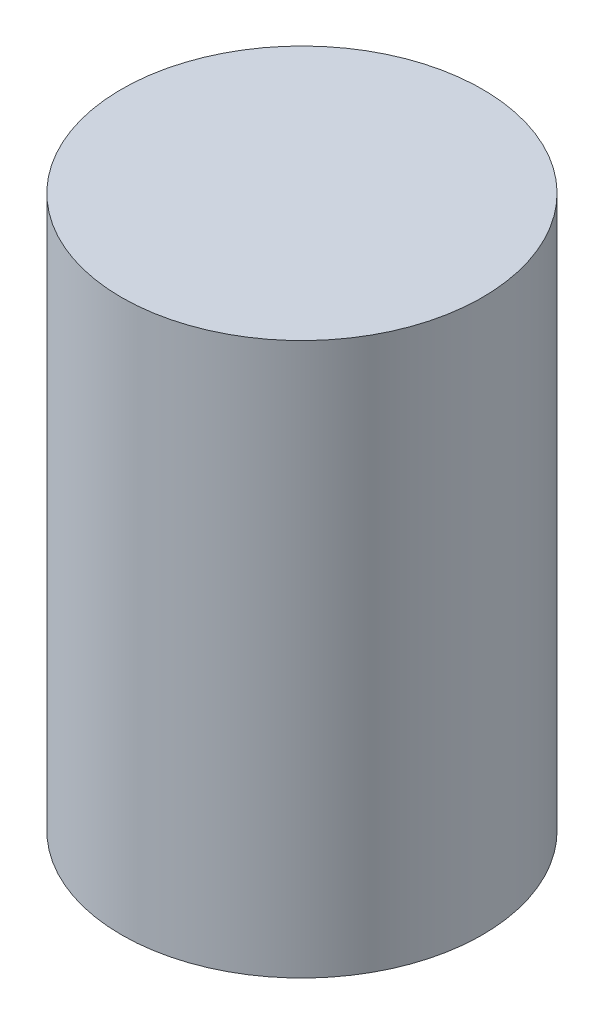
SolidWorks part; units mm, degrees
ref_plane "Front Plane" through (0, 0, 0) normal (0, 0, 1) x (1, 0, 0)
ref_plane "Top Plane" through (0, 0, 0) normal (0, 1, 0) x (1, 0, 0)
ref_plane "Right Plane" through (0, 0, 0) normal (1, 0, 0) x (0, 0, -1)
sketch "Sketch1" plane through (0, 0, 0) normal (0, 1, 0) x (1, 0, 0)
  circle A0 centre (0, 0) radius 4.65
  dimension "D1" = 9.3
extrude "Boss-Extrude1" add sketch "Sketch1" along normal blind 12
sketch "Sketch2" plane through (0, 12, 0) normal (0, 1, 0) x (1, 0, 0)
  circle A0 centre (0, 0) radius 17.5
  dimension "D1" = 35
extrude "Boss-Extrude2" add sketch "Sketch2" along normal blind 2
sketch "Sketch3" plane through (0, 14, 0) normal (0, 1, 0) x (1, 0, 0)
  line L0 (0, 0) -> (0, 17.5) construction
  line L2 (5, 6.5) -> (10, 6.5)
  line L3 (5, 6.5) -> (5, -6.5)
  line L4 (5, -6.5) -> (10, -6.5)
  line L5 (10, 6.5) -> (10, -6.5)
  circle A0 centre (0, 0) radius 17.5 construction
  point P9 (5, 0)
  dimension "D1" = 5
  dimension "D2" = 13
  dimension "D3" = 5
extrude "Boss-Extrude3" add sketch "Sketch3" along normal blind 12 contours L2 L5 L4 L3
mirror "Mirror1" about plane through (0, 0, 0) normal (1, 0, 0) of "Boss-Extrude3"
fillet "Fillet1" radius 4 4 edges at (-7.5, 26, -6.5) (7.5, 26, -6.5) (7.5, 26, 6.5) (-7.5, 26, 6.5)
fillet "Fillet2" radius 4 4 edges at (7.5, 14, -6.5) (-7.5, 14, -6.5) (-7.5, 14, 6.5) (7.5, 14, 6.5)
sketch "Sketch4" plane through (0, 14, 0) normal (0, 1, 0) x (1, 0, 0)
  line L0 (10, 0) -> (10, 14.3614)
  line L1 (10, 2.5) -> (10, -2.5) construction
  line L2 (10, 14.3614) -> (24.3824, 14.3614)
  line L3 (24.3824, 14.3614) -> (24.3824, -16.5205)
  line L4 (24.3824, -16.5205) -> (10, -16.5205)
  line L5 (10, -16.5205) -> (10, 0)
  circle A1 centre (0, 0) radius 17.5
  circle A2 centre (0, 0) radius 17.5
  circle M6 centre (0, 0) radius 17.5
  line M8 (10, 10.5) -> (10, -10.5)
  dimension "D1" = 0
extrude "Cut-Extrude1" cut sketch "Sketch4" against normal through all contours L5 L0 M6 M8
mirror "Mirror2" about plane through (0, 0, 0) normal (1, 0, 0) of "Cut-Extrude1"
sketch "Sketch5" plane through (10, 0, 0) normal (1, 0, 0) x (0, 0, -1)
  line L0 (-6.5, 22) -> (-6.5, 18) construction
  line L1 (2.5, 26) -> (-2.5, 26) construction
  circle A0 centre (0, 20) radius 2.05
  point P4 (-6.5, 20)
  point P7 (0, 26)
  dimension "D1" = 4.1
extrude "Cut-Extrude2" cut sketch "Sketch5" against normal blind 70
fillet "Fillet3" radius 4 4 edges at (10, 13, 14.3614) (10, 13, -14.3614) (-10, 13, -14.3614) (-10, 13, 14.3614)
sketch "Sketch6" plane through (0, 12, 0) normal (0, -1, 0) x (1, 0, 0)
  circle A0 centre (0, 0) radius 4.65 construction
  circle A1 centre (0, 0) radius 4.65
extrude "Cut-Extrude-Thin1" cut sketch "Sketch6" against normal through all thin
sketch "Sketch7" plane through (0, 14, 0) normal (0, 1, 0) x (1, 0, 0)
  circle A0 centre (0, 0) radius 4.575
  dimension "D1" = 9.15
extrude "Cut-Extrude-Thin2" cut sketch "Sketch7" against normal blind 30 thin
